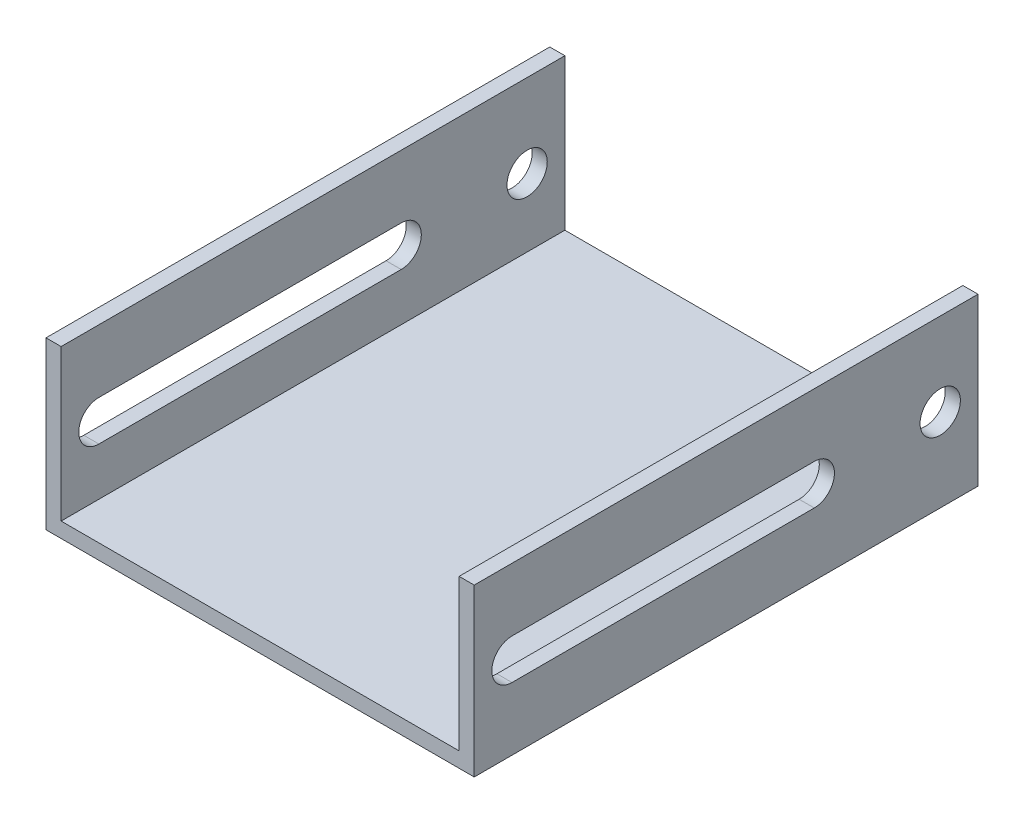
SolidWorks part; units mm, degrees
ref_plane "前视基准面" through (0, 0, 0) normal (0, 0, 1) x (1, 0, 0)
ref_plane "上视基准面" through (0, 0, 0) normal (0, 1, 0) x (1, 0, 0)
ref_plane "右视基准面" through (0, 0, 0) normal (1, 0, 0) x (0, 0, -1)
sketch "草图1" plane through (0, 0, 0) normal (0, 1, 0) x (1, 0, 0)
  line L1 (-42.5, -50) -> (42.5, -50)
  line L2 (-42.5, -50) -> (-42.5, 50)
  line L3 (-42.5, 50) -> (42.5, 50)
  line L4 (42.5, -50) -> (42.5, 50)
  line L5 (-42.5, -50) -> (42.5, 50) construction
  line L6 (-42.5, 50) -> (42.5, -50) construction
  point P0 (0, 0)
  dimension "D1" = 100
  dimension "D2" = 85
extrude "凸台-拉伸1" add sketch "草图1" along normal blind 3
sketch "草图2" plane through (0, 3, 0) normal (0, 1, 0) x (1, 0, 0)
  line L0 (-42.5, -50) -> (42.5, -50) construction
  line L1 (-42.5, 50) -> (-39.5, 50)
  line L2 (-42.5, 50) -> (-42.5, -50)
  line L3 (-42.5, -50) -> (-39.5, -50)
  line L4 (-39.5, 50) -> (-39.5, -50)
  line L5 (42.5, 50) -> (-42.5, 50) construction
  line L6 (42.5, -50) -> (39.5, -50)
  line L7 (42.5, -50) -> (42.5, 50)
  line L8 (42.5, 50) -> (39.5, 50)
  line L9 (39.5, -50) -> (39.5, 50)
  dimension "D1" = 3
  dimension "D2" = 3
extrude "凸台-拉伸2" add sketch "草图2" along normal blind 30
sketch "草图3" plane through (42.5, 0, 0) normal (1, 0, 0) x (0, 0, -1)
  line L0 (-50, 16.5) -> (50, 16.5) construction
  line L1 (-50, 33) -> (-50, 0) construction
  line L2 (50, 33) -> (50, 0) construction
  line L4 (-42.5, 12.5) -> (17.5, 12.5)
  line L5 (-42.5, 12.5) -> (-42.5, 20.5) construction
  line L6 (-42.5, 20.5) -> (17.5, 20.5)
  line L7 (17.5, 12.5) -> (17.5, 20.5) construction
  line L8 (-42.5, 12.5) -> (17.5, 20.5) construction
  line L9 (-42.5, 20.5) -> (17.5, 12.5) construction
  circle A0 centre (42.5, 16.5) radius 4
  arc A1 (17.5, 12.5) -> (17.5, 20.5) centre (17.5, 16.5) ccw
  arc A2 (-42.5, 20.5) -> (-42.5, 12.5) centre (-42.5, 16.5) ccw
  point P8 (-12.5, 16.5)
  dimension "D1" = 8
  dimension "D2" = 4
  dimension "D3" = 60
  dimension "D4" = 85
  dimension "D5" = 7.5
extrude "切除-拉伸1" cut sketch "草图3" against normal up to surface (85 mm away) up to face at (-42.5, 16.5, 0)
